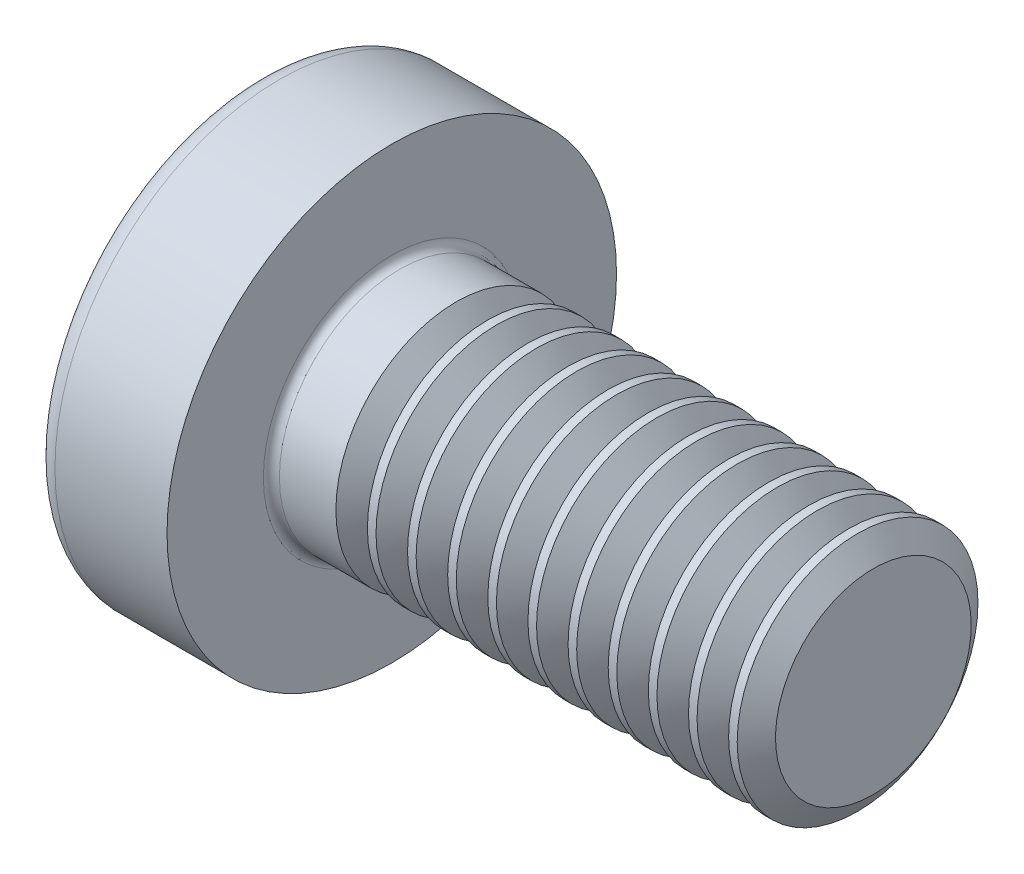
SolidWorks part; units mm, degrees
ref_plane "Plane1" through (0, 0, 0) normal (0, 0, 1) x (1, 0, 0)
ref_plane "Plane2" through (0, 0, 0) normal (0, 1, 0) x (1, 0, 0)
ref_plane "Plane3" through (0, 0, 0) normal (1, 0, 0) x (0, 0, -1)
sketch "BodySke" plane through (0, 0, 0) normal (0, 0, 1) x (1, 0, 0)
  line L0 (2.4, 1.5) -> (2.4, 2.8)
  line L1 (2.65, 6.35) -> (2.65, -3.175) construction
  line L2 (-25.4, 0) -> (127, 0) construction
  line L3 (8.4, 0) -> (0, 0)
  line L4 (2.4, 1.5) -> (8.4, 1.5)
  line L5 (8.4, 1.5) -> (8.4, 0)
  line L6 (1.0035, 2.8) -> (2.4, 2.8)
  line L8 (2.4, 6.35) -> (2.4, -3.175) construction
  arc A0 (0.7754, 2.6744) -> (0, 0) centre (5, 0) ccw
  arc A2 (0.7754, 2.6744) -> (1.0035, 2.8) centre (1.0035, 2.53) cw
  dimension "Head_fillet_rad" = 0.27
  dimension "Head_crown_rad" = 5
  dimension "Head_ht" = 2.4
  dimension "Diameter" = 3
  dimension "Length" = 6
  dimension "Head_dia" = 5.6
  dimension "Advance" = 0.5
  dimension "Thread_nom" = 6
revolve "Base-Revolve" add sketch "BodySke"
cosmetic thread "ThreadCosmetic" [suppressed]
fillet "Fillet1" radius 0.1 1 edges at (2.4, 0, 1.5)
sketch "Sketch3" plane through (0, 0, 0) normal (1, 0, 0) x (0, 0, -1)
  line L0 (0.37, -1.4) -> (-0.37, -1.4)
  line L1 (0.37, -1.4) -> (0.37, 1.4)
  line L2 (-0.37, 1.4) -> (0.37, 1.4)
  line L3 (-0.37, 1.4) -> (-0.37, -1.4)
  dimension "D1" = 1.4
  dimension "Cross_dia" = 2.8
  dimension "D2" = 0.37
  dimension "Cross_width" = 0.74
ref_plane "Plane4" through (1.75, 0, 0) normal (1, 0, 0) x (0, 0, -1)
sketch "Sketch4" plane through (1.75, 0, 0) normal (1, 0, 0) x (0, 0, -1)
  line L0 (0.37, -0.5275) -> (-0.37, -0.5275)
  line L1 (0.37, -0.5275) -> (0.37, 0.5275)
  line L2 (-0.37, 0.5275) -> (0.37, 0.5275)
  line L3 (-0.37, 0.5275) -> (-0.37, -0.5275)
  dimension "D1" = 0.74
  dimension "D2" = 1.055
  dimension "D3" = 0.37
  dimension "D4" = 0.5275
loft "Recess" cut profiles "Sketch3", "Sketch4"
pattern_circular "RecPat" count 2 every 90 about axis through (0, 0, 0) along (1, 0, 0) of "Recess"
sketch "RecCorSke" plane through (0, 0, 0) normal (0, 0, 1) x (1, 0, 0)
  line L0 (-3.175, 0) -> (15.875, 0) construction
  line L1 (-25.4, 0) -> (127, 0) construction
  line L2 (0, 0) -> (0, 0.6784)
  line L3 (0, 0.6784) -> (1.75, 0.556)
  line L4 (1.75, 0.556) -> (1.9307, 0)
  line L5 (1.9307, 0) -> (0, 0)
  dimension "Diameter" = 1.112
  dimension "Depth" = 1.75
  dimension "Draft_angle" = 4
  dimension "Bottom_angle" = 18
revolve "RecessCore" cut sketch "RecCorSke" angle 360 about L0
sketch "ThdSchSke" plane through (0, 0, 0) normal (0, 0, 1) x (1, 0, 0)
  line L0 (3.4, -1.2195) -> (3.2036, -1.5)
  line L1 (3.4, -1.2195) -> (3.5964, -1.5)
  line L2 (3.5964, -1.5) -> (3.5964, -1.875)
  line L3 (-3.175, 0) -> (5.1513, 0) construction
  line L5 (3.5964, -1.875) -> (3.2036, -1.875)
  line L6 (3.2036, -1.875) -> (3.2036, -1.5)
  dimension "Thread_minor" = 2.439
  dimension "Diameter" = 3
  dimension "Start" = 3.4
  dimension "SideAngle" = 55
  dimension "VeeAngle" = 70
  dimension "Overcut" = 3.75
revolve "ThreadSchematic" cut sketch "ThdSchSke" angle 360 about L3
pattern_linear "ThdSchPat" count 11 spacing 0.5 along (1, 0, 0) of "ThreadSchematic"
equation "\"D1@Sketch3\" = \"Cross_dia@Sketch3\" / 2"
equation "\"D2@Sketch3\" = \"Cross_width@Sketch3\" / 2"
equation "\"Depth@RecCorSke\" = \"Cross_depth@Plane4\""
equation "\"D1@Sketch4\" = \"Cross_width@Sketch3\""
equation "\"D2@Sketch4\" = \"Cross_dia@Sketch3\" - 2.0 * \"Cross_depth@Plane4\" * tan(26.5  * 0.017453292)"
equation "\"D3@Sketch4\" = \"D1@Sketch4\" / 2"
equation "\"D4@Sketch4\" = \"D2@Sketch4\" / 2"
equation "\"Thread_length@ThreadCosmetic\" = ((sgn( (\"Length@BodySke\" - \"Advance@BodySke\" * 2.0 ) - \"Thread_nom@BodySke\" )-1)*( (\"Length@BodySke\" - \"Advance@BodySke\" * 2.0 ) - \"Thread_nom@BodySke\" ))/-2+ \"Thread_nom@BodySke\""
equation "\"Thread_minor@ThdSchSke\" = \"Thread_minor@ThreadCosmetic\""
equation "\"Diameter@ThdSchSke\" = \"Diameter@BodySke\""
equation "\"Overcut@ThdSchSke\" = \"Diameter@BodySke\" * 1.25"
equation "\"Start@ThdSchSke\" = \"Head_ht@BodySke\" + \"Length@BodySke\" - \"Thread_length@ThreadCosmetic\"  '---Non-countersunk---"
equation "\"Num_threads@ThdSchPat\" = int( \"Thread_length@ThreadCosmetic\" / \"Advance@BodySke\" + 0.999 )  + 1"
equation "\"Advance@ThdSchPat\" = \"Thread_length@ThreadCosmetic\" /  (\"Num_threads@ThdSchPat\" - 1) 'relax it"
